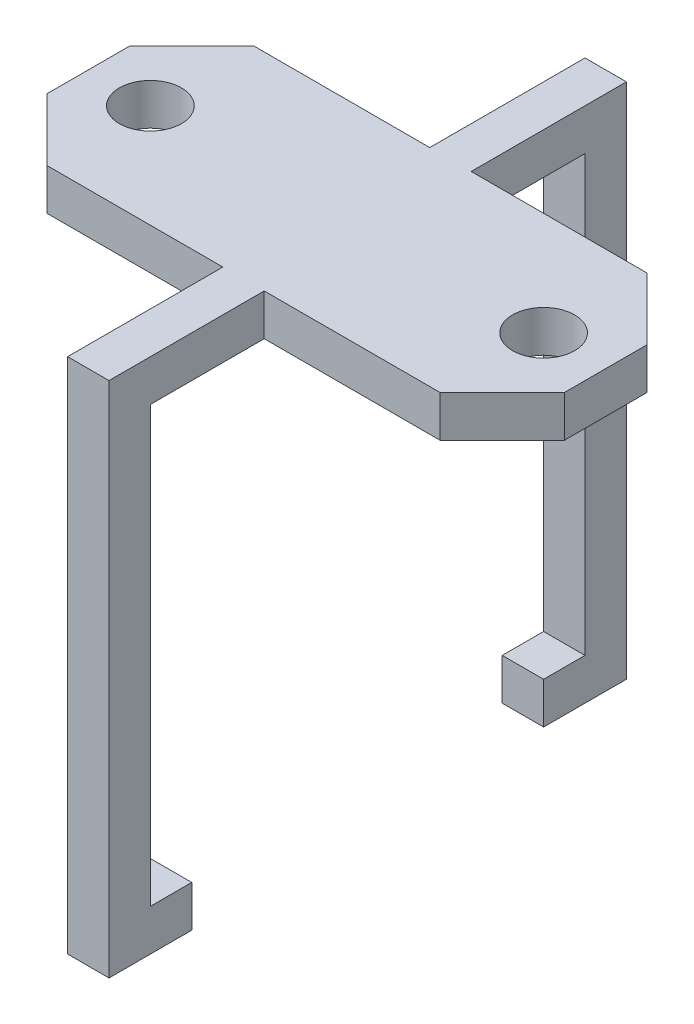
SolidWorks part; units mm, degrees
other "PrintSupporter"
ref_plane "정면" through (0, 0, 0) normal (0, 0, 1) x (1, 0, 0)
ref_plane "윗면" through (0, 0, 0) normal (0, 1, 0) x (1, 0, 0)
ref_plane "우측면" through (0, 0, 0) normal (1, 0, 0) x (0, 0, -1)
sketch "스케치1" plane through (0, 0, 0) normal (0, 1, 0) x (1, 0, 0)
  line L0 (-9.5, 0) -> (9.5, 0) construction
  line L2 (-12.5, -5) -> (12.5, -5)
  line L3 (-12.5, -5) -> (-12.5, 5)
  line L4 (-12.5, 5) -> (12.5, 5)
  line L5 (12.5, -5) -> (12.5, 5)
  line L6 (-12.5, -5) -> (12.5, 5) construction
  line L7 (-12.5, 5) -> (12.5, -5) construction
  circle A0 centre (-9.5, 0) radius 1.5
  circle A1 centre (9.5, 0) radius 1.5
  point P4 (0, 0)
  point P7 (0, 0)
  dimension "D2" = 3
  dimension "D1" = 19
  dimension "D3" = 25
  dimension "D4" = 10
extrude "보스-돌출1" add sketch "스케치1" along normal blind 2
sketch "스케치4" plane through (0, 0, 0) normal (1, 0, 0) x (0, 0, -1)
  line L0 (-5, 0) -> (5, 0) construction
  line L1 (-10.5, 0) -> (10.5, 0)
  line L2 (-10.5, 0) -> (-10.5, -21)
  line L3 (-10.5, -21) -> (-8.5, -21)
  line L4 (10.5, 0) -> (10.5, -21)
  line L6 (-12.5, 0) -> (12.5, 0)
  line L7 (-12.5, 0) -> (-12.5, -23)
  line L8 (-12.5, -23) -> (-8.5, -23)
  line L9 (12.5, 0) -> (12.5, -23)
  line L10 (-12.5, 0) -> (-5, 0)
  line L11 (5, 2) -> (5, 0)
  line L12 (-5, 2) -> (-5, 0)
  line L13 (8.5, -21) -> (10.5, -21)
  line L14 (-12.5, 0) -> (-12.5, 2)
  line L15 (-8.5, -23) -> (-8.5, -21)
  line L16 (-12.5, 2) -> (-5, 2)
  line L17 (8.5, -23) -> (8.5, -21)
  line L18 (-5, 0) -> (-5, 2)
  line L20 (8.5, -23) -> (12.5, -23)
  line L21 (5, 2) -> (12.5, 2)
  line L22 (5, 2) -> (5, 0)
  line L23 (5, 0) -> (12.5, 0)
  line L24 (12.5, 2) -> (12.5, 0)
  point P4 (0, -21)
  point P12 (0, -23)
  point P16 (0, -21)
  dimension "D1" = 21
  dimension "D2" = 2
  dimension "D3" = 2
  dimension "D4" = 2
  dimension "D5" = 4
extrude "보스-돌출3" add sketch "스케치4" along normal mid plane 2
chamfer "모따기1" distance 3 angle 45 4 edges at (12.5, 1, -5) (12.5, 1, 5) (-12.5, 1, -5) (-12.5, 1, 5)
sketch "스케치5" plane through (0, 2, 0) normal (0, 1, 0) x (1, 0, 0)
  line L0 (-12.5, 0) -> (12.5, 0) construction
  line L1 (-12.5, 2) -> (-12.5, -2) construction
  line L2 (12.5, -2) -> (12.5, 2) construction
  line L3 (1, -12.5) -> (-1, -12.5) construction
  line L4 (0, -12.5) -> (0, 12.5) construction
  circle A0 centre (0, -12.5) radius 5
  circle A1 centre (0, 12.5) radius 5
  circle A2 centre (9.5, -5) radius 1.5
  circle A3 centre (9.5, 5) radius 1.5
  circle A4 centre (-9.5, -5) radius 1.5
  circle A5 centre (-9.5, 5) radius 1.5
  circle A6 centre (12.5, -2) radius 1.5
  circle A7 centre (12.5, 2) radius 1.5
  circle A8 centre (-12.5, -2) radius 1.5
  circle A9 centre (-12.5, 2) radius 1.5
  dimension "D1" = 10
  dimension "D2" = 3
extrude "보스-돌출4" [suppressed] add sketch "스케치5" against normal blind 0.4
